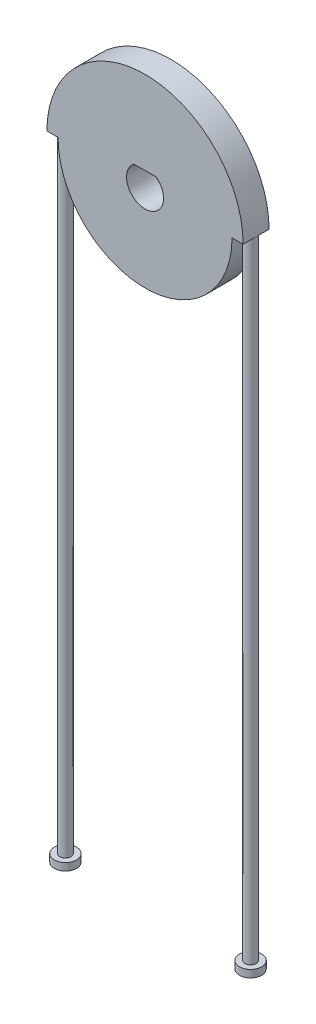
SolidWorks part; units mm, degrees
material "Acrylic (Medium-high impact)"
ref_plane "Front Plane" through (0, 0, 0) normal (0, 0, 1) x (1, 0, 0)
ref_plane "Top Plane" through (0, 0, 0) normal (0, 1, 0) x (1, 0, 0)
ref_plane "Right Plane" through (0, 0, 0) normal (1, 0, 0) x (0, 0, -1)
sketch "Sketch2" plane through (0, 0, 0) normal (1, 0, 0) x (0, 0, -1)
  line L0 (-3.562, 0) -> (3.438, 0)
  line L1 (0, 20.2833) -> (0, -16.4952) construction
  line L2 (-3.562, 0) -> (-3.562, 26.5)
  line L3 (3.438, 0) -> (3.438, 26.5)
  line L4 (-3.562, 26.5) -> (-1.562, 26.5)
  line L5 (3.438, 26.5) -> (1.438, 26.5)
  line L8 (1.438, 26.5) -> (-1.562, 26.5)
  dimension "D1" = 7
  dimension "D2" = 26.5
  dimension "D3" = 2
  dimension "D4" = 2
  dimension "D5" = 26.5
revolve "Revolve1" add sketch "Sketch2" angle 360 about L0
sketch "Sketch3" plane through (0, 0, -3.438) normal (0, 0, -1) x (-1, 0, 0)
  line L0 (0, 0) -> (0, 7.3583) construction
  line L1 (-10.3695, 4.1123) -> (10.8046, 3.8835) construction
  line L2 (-2.9566, 4.0322) -> (3.043, 3.9674)
  circle A0 centre (0, 0) radius 5 construction
  arc A1 (-2.9566, 4.0322) -> (3.043, 3.9674) centre (0, 0) ccw
  dimension "D2" = 10
  dimension "D1" = 4
extrude "Cut-Extrude1" cut sketch "Sketch3" against normal blind 9
sketch "Sketch5" plane through (0, 0, -3.438) normal (0, 0, -1) x (-1, 0, 0)
  line L0 (-42.8178, 0) -> (43.9596, 0) construction
  line L1 (-26.5, 0) -> (-23.5, 0)
  line L2 (23.5, 0) -> (26.5, 0)
  arc A0 (-26.5, 0) -> (26.5, 0) centre (0, 0) ccw
  arc A1 (-23.5, 0) -> (23.5, 0) centre (0, 0) ccw
extrude "Cut-Extrude2" cut sketch "Sketch5" against normal blind 7
sketch "Sketch6" plane through (0, 0, 0) normal (0, -1, 0) x (1, 0, 0)
  line L0 (-23.5, 3.562) -> (-23.5, -3.438) construction
  line L1 (-26.5, -3.438) -> (-23.5, -3.438) construction
  line L2 (23.5, 3.562) -> (23.5, -3.438) construction
  line L3 (23.5, -3.438) -> (26.5, -3.438) construction
  circle A0 centre (25, 0.062) radius 1.5
  circle A1 centre (-25, 0.062) radius 1.5
  dimension "D1" = 1.5
  dimension "D2" = 3.5
  dimension "D3" = 1.5
  dimension "D4" = 3.5
extrude "Boss-Extrude1" add sketch "Sketch6" along normal blind 170
sketch "Sketch7" plane through (0, -170, 0) normal (0, -1, 0) x (1, 0, 0)
  circle A0 centre (25, 0.062) radius 3
  circle A1 centre (-25, 0.062) radius 3
extrude "Boss-Extrude2" add sketch "Sketch7" along normal blind 2
